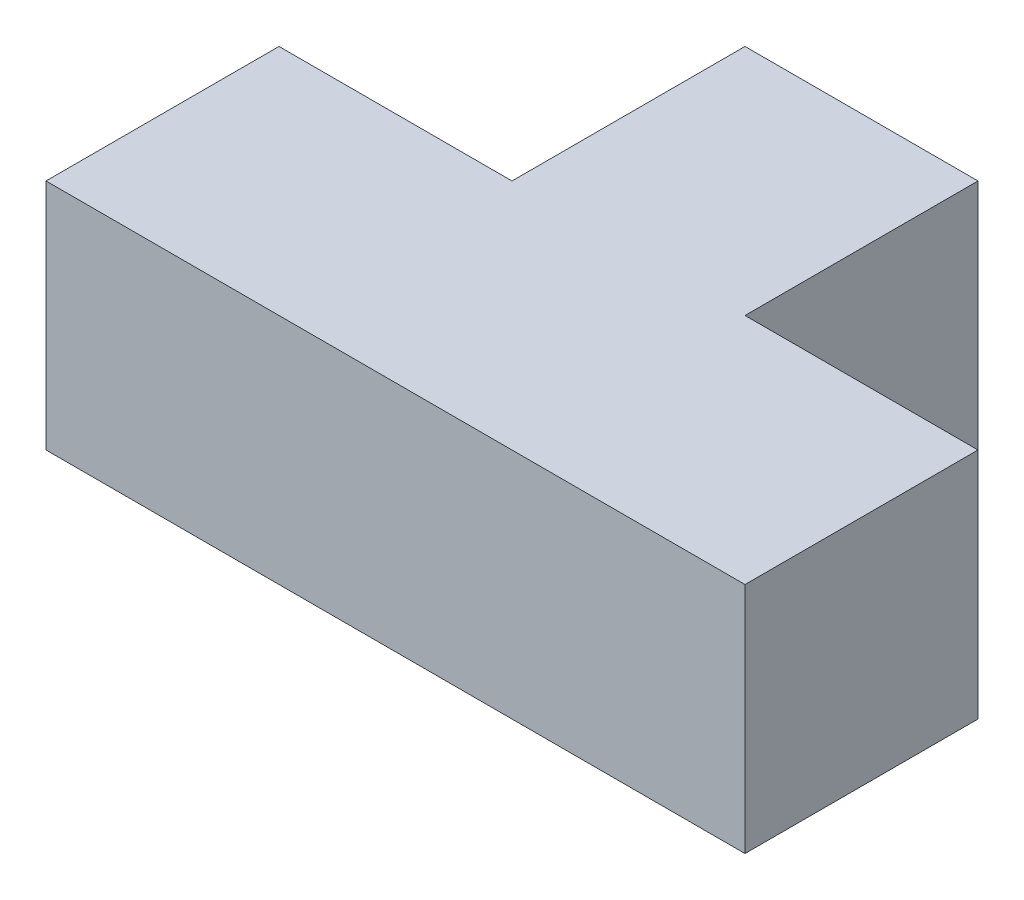
SolidWorks part; units mm, degrees
ref_plane "前视基准面" through (0, 0, 0) normal (0, 0, 1) x (1, 0, 0)
ref_plane "上视基准面" through (0, 0, 0) normal (0, 1, 0) x (1, 0, 0)
ref_plane "右视基准面" through (0, 0, 0) normal (1, 0, 0) x (0, 0, -1)
other "Configuration Table"
sketch "草图1" plane through (0, 0, 0) normal (0, 1, 0) x (1, 0, 0)
  line L0 (0, 0) -> (200, 0)
  line L1 (200, 0) -> (200, 100)
  line L2 (200, 100) -> (100, 100)
  line L3 (100, 100) -> (100, 200)
  line L4 (100, 200) -> (0, 200)
  line L5 (0, 200) -> (0, 0)
  dimension "D1" = 200
  dimension "D2" = 200
  dimension "D3" = 100
  dimension "D4" = 100
  dimension "D5" = 100
extrude "凸台-拉伸1" add sketch "草图1" along normal blind 100 contours L4 L5 L0 L1 L2 L3
sketch "草图3" plane through (0, 0, 0) normal (-1, 0, 0) x (0, 0, 1)
  line L4 (-100, 0) -> (0, 0)
  line L5 (-100, 100) -> (-100, 0)
  line L6 (0, 100) -> (-100, 100)
  line L7 (0, 0) -> (0, 100)
  line L8 (-100, 0) -> (0, 0)
  line L9 (-100, 100) -> (-100, 0)
  line L10 (0, 100) -> (-100, 100)
  line L11 (0, 0) -> (0, 100)
  dimension "D1" = 0
extrude "凸台-拉伸3" add sketch "草图3" along normal blind 100
